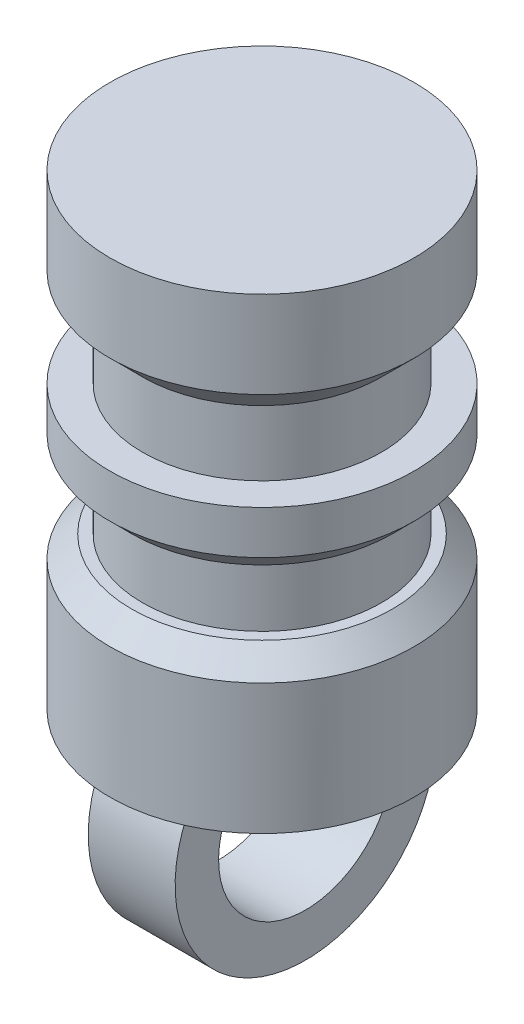
SolidWorks part; units mm, degrees
ref_plane "Alzado" through (0, 0, 0) normal (0, 0, 1) x (1, 0, 0)
ref_plane "Planta" through (0, 0, 0) normal (0, 1, 0) x (1, 0, 0)
ref_plane "Vista lateral" through (0, 0, 0) normal (1, 0, 0) x (0, 0, -1)
sketch "Croquis1" plane through (0, 0, 0) normal (0, 1, 0) x (1, 0, 0)
  line L1 (-18.35, -20) -> (18.35, -20)
  line L2 (-18.35, -20) -> (-18.35, 20)
  line L3 (-18.35, 20) -> (18.35, 20)
  line L4 (18.35, -20) -> (18.35, 20)
  line L5 (-18.35, -20) -> (18.35, 20) construction
  line L6 (-18.35, 20) -> (18.35, -20) construction
  circle A0 centre (0, 0) radius 4
  point P0 (0, 0)
  dimension "D3" = 8
  dimension "D1" = 36.7
  dimension "D2" = 40
extrude "Saliente-Extruir1" add sketch "Croquis1" along normal blind 7
sketch "Croquis2" plane through (0, 0, 0) normal (1, 0, 0) x (0, 0, -1)
  line L1 (4, 7) -> (0, 7) construction
  line L2 (0, 7) -> (0, 17.1204) construction
  line L3 (7, 7) -> (7, 12)
  line L4 (7, 12) -> (5.5, 12)
  line L5 (5.5, 12) -> (5.5, 15)
  line L6 (5.5, 15) -> (7, 15)
  line L7 (7, 15) -> (7, 18)
  line L8 (7, 18) -> (5.5, 18)
  line L9 (5.5, 18) -> (5.5, 21)
  line L10 (5.5, 21) -> (7, 22.5)
  line L11 (7, 22.5) -> (7, 24.5)
  line L12 (20, 7) -> (-20, 7) construction
  line L13 (4, 7) -> (4, 24.5)
  line L14 (4, 7) -> (-4, 7) construction
  line L15 (4, 7) -> (-4, 7) construction
  line L16 (7, 24.5) -> (4, 24.5)
  line L17 (4, 7) -> (7, 7)
  dimension "D1" = 5
  dimension "D2" = 3
  dimension "D3" = 3
  dimension "D4" = 3
  dimension "D5" = 1.5
  dimension "D6" = 7
  dimension "D7" = 5.5
  dimension "D8" = 2
revolve "Revolución1" add sketch "Croquis2" angle 360 about L2
chamfer "Chaflán1" distance 1 angle 45 2 edges at (0, 12, -7) (0, 15, -7)
sketch "Croquis3" plane through (0, 0, 0) normal (0, -1, 0) x (1, 0, 0)
  circle A0 centre (0, 0) radius 6.55
  dimension "D1" = 13.1
extrude "Cortar-Extruir1" cut sketch "Croquis3" against normal blind 2
sketch "Croquis5" plane through (0, 0, 20) normal (0, 0, 1) x (1, 0, 0)
  line L1 (-18.35, 7) -> (18.35, 7)
  line L2 (-18.35, 7) -> (-18.35, 0)
  line L3 (-18.35, 0) -> (18.35, 0)
  line L4 (18.35, 7) -> (18.35, 0)
extrude "Cortar-Extruir2" cut sketch "Croquis5" against normal through all
sketch "Croquis6" plane through (0, 7, 0) normal (0, -1, 0) x (1, 0, 0)
  circle A0 centre (0, 0) radius 7
extrude "Saliente-Extruir2" add sketch "Croquis6" along normal blind 2
sketch "Croquis7" plane through (0, 24.5, 0) normal (0, 1, 0) x (1, 0, 0)
  circle A0 centre (0, 0) radius 7
extrude "Saliente-Extruir3" add sketch "Croquis7" along normal blind 2
sketch "Croquis8" plane through (0, 0, 0) normal (1, 0, 0) x (0, 0, -1)
  line L0 (0, 5) -> (0, 2) construction
  line L2 (-7, 5) -> (7, 5) construction
  line L3 (-5.1962, 5) -> (0, 5)
  line L4 (2.6458, 5) -> (5.1962, 5)
  arc A1 (-2.6458, 5) -> (2.6458, 5) centre (0, 2) ccw
  arc A2 (-5.1962, 5) -> (5.1962, 5) centre (0, 2) ccw
  circle A3 centre (0, 2) radius 6 construction
  circle A4 centre (0, 2) radius 4 construction
  point P5 (-5.354, 5)
  dimension "D1" = 8
  dimension "D3" = 3
  dimension "D2" = 2
extrude "Saliente-Extruir4" add sketch "Croquis8" along normal mid plane 4 contours L3 A2 L4 A1
